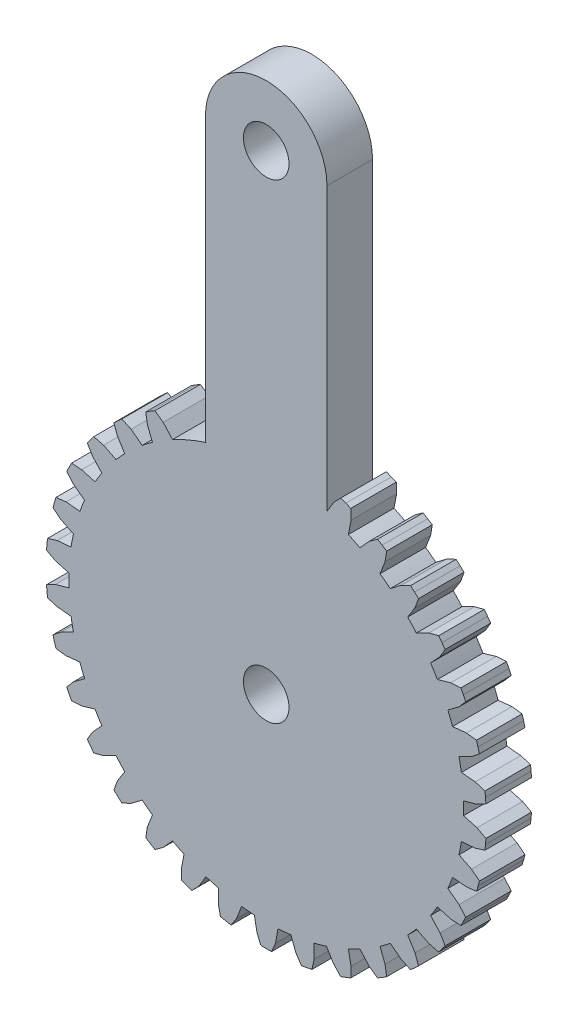
SolidWorks part; units mm, degrees
material "Chrome Stainless Steel"
ref_plane "Front Plane" through (0, 0, 0) normal (0, 0, 1) x (1, 0, 0)
ref_plane "Top Plane" through (0, 0, 0) normal (0, 1, 0) x (1, 0, 0)
ref_plane "Right Plane" through (0, 0, 0) normal (1, 0, 0) x (0, 0, -1)
sketch "Sketch1" plane through (0, 0, 0) normal (0, 0, 1) x (1, 0, 0)
  line L0 (0, 13) -> (0, 14.5) construction
  line L1 (-0.7768, 12.9768) -> (-0.6124, 13.879)
  line L2 (-0.6124, 13.879) -> (-0.3549, 14.4957)
  line L3 (-0.3549, 14.4957) -> (0, 14.5)
  line L4 (0.3549, 14.4957) -> (0, 14.5)
  line L5 (0.7768, 12.9768) -> (0.6124, 13.879)
  line L6 (0.6124, 13.879) -> (0.3549, 14.4957)
  line L7 (1.9483, 13.7552) -> (2.3147, 14.3141)
  line L8 (1.6209, 12.8986) -> (1.9483, 13.7552)
  line L9 (3.1522, 13.5302) -> (3.0124, 14.1836)
  line L10 (3.148, 12.6131) -> (3.1522, 13.5302)
  line L11 (3.0124, 14.1836) -> (2.6644, 14.2531)
  line L12 (2.3147, 14.3141) -> (2.6644, 14.2531)
  line L13 (4.4426, 13.163) -> (4.9055, 13.645)
  line L14 (3.9634, 12.3811) -> (4.4426, 13.163)
  line L15 (5.5847, 12.7206) -> (5.5674, 13.3886)
  line L16 (5.4121, 11.8199) -> (5.5847, 12.7206)
  line L17 (5.5674, 13.3886) -> (5.238, 13.5208)
  line L18 (4.9055, 13.645) -> (5.238, 13.5208)
  line L19 (6.7857, 12.1225) -> (7.3292, 12.5113)
  line L20 (6.1709, 11.442) -> (6.7857, 12.1225)
  line L21 (7.827, 11.4778) -> (7.9327, 12.1376)
  line L22 (7.4918, 10.6241) -> (7.827, 11.4778)
  line L23 (7.9327, 12.1376) -> (7.6333, 12.3281)
  line L24 (7.3292, 12.5113) -> (7.6333, 12.3281)
  line L25 (8.8977, 10.6693) -> (9.5034, 10.9515)
  line L26 (8.1683, 10.1133) -> (8.8977, 10.6693)
  line L27 (9.8028, 9.8441) -> (10.0279, 10.4733)
  line L28 (9.3165, 9.0666) -> (9.8028, 9.8441)
  line L29 (10.0279, 10.4733) -> (9.7686, 10.7156)
  line L30 (9.5034, 10.9515) -> (9.7686, 10.7156)
  line L31 (10.7066, 8.8526) -> (11.3539, 9.0188)
  line L32 (9.8876, 8.4402) -> (10.7066, 8.8526)
  line L33 (11.4447, 7.8753) -> (11.7817, 8.4524)
  line L34 (10.8238, 7.2004) -> (11.4447, 7.8753)
  line L35 (11.7817, 8.4524) -> (11.5712, 8.7382)
  line L36 (11.3539, 9.0188) -> (11.5712, 8.7382)
  line L37 (12.151, 6.7346) -> (12.8178, 6.779)
  line L38 (11.2701, 6.4796) -> (12.151, 6.7346)
  line L39 (12.6969, 5.6382) -> (13.1342, 6.1436)
  line L40 (11.9626, 5.0889) -> (12.6969, 5.6382)
  line L41 (13.1342, 6.1436) -> (12.9799, 6.4632)
  line L42 (12.8178, 6.779) -> (12.9799, 6.4632)
  line L43 (13.1816, 4.3872) -> (13.8452, 4.3083)
  line L44 (12.2688, 4.2984) -> (13.1816, 4.3872)
  line L45 (13.5168, 3.2092) -> (14.0394, 3.6256)
  line L46 (12.694, 2.8041) -> (13.5168, 3.2092)
  line L47 (14.0394, 3.6256) -> (13.9465, 3.9681)
  line L48 (13.8452, 4.3083) -> (13.9465, 3.9681)
  line L49 (13.7633, 1.8904) -> (14.4011, 1.6909)
  line L50 (12.8497, 1.9708) -> (13.7633, 1.8904)
  line L51 (13.8763, 0.6708) -> (14.4666, 0.9841)
  line L52 (12.9931, 0.4239) -> (13.8763, 0.6708)
  line L53 (14.4666, 0.9841) -> (14.4381, 1.3379)
  line L54 (14.4011, 1.6909) -> (14.4381, 1.3379)
  line L55 (13.8763, -0.6708) -> (14.4666, -0.9841)
  line L56 (12.9931, -0.4239) -> (13.8763, -0.6708)
  line L57 (13.7633, -1.8904) -> (14.4011, -1.6909)
  line L58 (12.8497, -1.9708) -> (13.7633, -1.8904)
  line L59 (14.4011, -1.6909) -> (14.4381, -1.3379)
  line L60 (14.4666, -0.9841) -> (14.4381, -1.3379)
  line L61 (13.5168, -3.2092) -> (14.0394, -3.6256)
  line L62 (12.694, -2.8041) -> (13.5168, -3.2092)
  line L63 (13.1816, -4.3872) -> (13.8452, -4.3083)
  line L64 (12.2688, -4.2984) -> (13.1816, -4.3872)
  line L65 (13.8452, -4.3083) -> (13.9465, -3.9681)
  line L66 (14.0394, -3.6256) -> (13.9465, -3.9681)
  line L67 (12.6969, -5.6382) -> (13.1342, -6.1436)
  line L68 (11.9626, -5.0889) -> (12.6969, -5.6382)
  line L69 (12.151, -6.7346) -> (12.8178, -6.779)
  line L70 (11.2701, -6.4796) -> (12.151, -6.7346)
  line L71 (12.8178, -6.779) -> (12.9799, -6.4632)
  line L72 (13.1342, -6.1436) -> (12.9799, -6.4632)
  line L73 (11.4447, -7.8753) -> (11.7817, -8.4524)
  line L74 (10.8238, -7.2004) -> (11.4447, -7.8753)
  line L75 (10.7066, -8.8526) -> (11.3539, -9.0188)
  line L76 (9.8876, -8.4402) -> (10.7066, -8.8526)
  line L77 (11.3539, -9.0188) -> (11.5712, -8.7382)
  line L78 (11.7817, -8.4524) -> (11.5712, -8.7382)
  line L79 (9.8028, -9.8441) -> (10.0279, -10.4733)
  line L80 (9.3165, -9.0666) -> (9.8028, -9.8441)
  line L81 (8.8977, -10.6693) -> (9.5034, -10.9515)
  line L82 (8.1683, -10.1133) -> (8.8977, -10.6693)
  line L83 (9.5034, -10.9515) -> (9.7686, -10.7156)
  line L84 (10.0279, -10.4733) -> (9.7686, -10.7156)
  line L85 (7.827, -11.4778) -> (7.9327, -12.1376)
  line L86 (7.4918, -10.6241) -> (7.827, -11.4778)
  line L87 (6.7857, -12.1225) -> (7.3292, -12.5113)
  line L88 (6.1709, -11.442) -> (6.7857, -12.1225)
  line L89 (7.3292, -12.5113) -> (7.6333, -12.3281)
  line L90 (7.9327, -12.1376) -> (7.6333, -12.3281)
  line L91 (5.5847, -12.7206) -> (5.5674, -13.3886)
  line L92 (5.4121, -11.8199) -> (5.5847, -12.7206)
  line L93 (4.4426, -13.163) -> (4.9055, -13.645)
  line L94 (3.9634, -12.3811) -> (4.4426, -13.163)
  line L95 (4.9055, -13.645) -> (5.238, -13.5208)
  line L96 (5.5674, -13.3886) -> (5.238, -13.5208)
  line L97 (3.1522, -13.5302) -> (3.0124, -14.1836)
  line L98 (3.148, -12.6131) -> (3.1522, -13.5302)
  line L99 (1.9483, -13.7552) -> (2.3147, -14.3141)
  line L100 (1.6209, -12.8986) -> (1.9483, -13.7552)
  line L101 (2.3147, -14.3141) -> (2.6644, -14.2531)
  line L102 (3.0124, -14.1836) -> (2.6644, -14.2531)
  line L103 (0.6124, -13.879) -> (0.3549, -14.4957)
  line L104 (0.7768, -12.9768) -> (0.6124, -13.879)
  line L105 (-0.6124, -13.879) -> (-0.3549, -14.4957)
  line L106 (-0.7768, -12.9768) -> (-0.6124, -13.879)
  line L107 (-0.3549, -14.4957) -> (0, -14.5)
  line L108 (0.3549, -14.4957) -> (0, -14.5)
  line L109 (-1.9483, -13.7552) -> (-2.3147, -14.3141)
  line L110 (-1.6209, -12.8986) -> (-1.9483, -13.7552)
  line L111 (-3.1522, -13.5302) -> (-3.0124, -14.1836)
  line L112 (-3.148, -12.6131) -> (-3.1522, -13.5302)
  line L113 (-3.0124, -14.1836) -> (-2.6644, -14.2531)
  line L114 (-2.3147, -14.3141) -> (-2.6644, -14.2531)
  line L115 (-4.4426, -13.163) -> (-4.9055, -13.645)
  line L116 (-3.9634, -12.3811) -> (-4.4426, -13.163)
  line L117 (-5.5847, -12.7206) -> (-5.5674, -13.3886)
  line L118 (-5.4121, -11.8199) -> (-5.5847, -12.7206)
  line L119 (-5.5674, -13.3886) -> (-5.238, -13.5208)
  line L120 (-4.9055, -13.645) -> (-5.238, -13.5208)
  line L121 (-6.7857, -12.1225) -> (-7.3292, -12.5113)
  line L122 (-6.1709, -11.442) -> (-6.7857, -12.1225)
  line L123 (-7.827, -11.4778) -> (-7.9327, -12.1376)
  line L124 (-7.4918, -10.6241) -> (-7.827, -11.4778)
  line L125 (-7.9327, -12.1376) -> (-7.6333, -12.3281)
  line L126 (-7.3292, -12.5113) -> (-7.6333, -12.3281)
  line L127 (-8.8977, -10.6693) -> (-9.5034, -10.9515)
  line L128 (-8.1683, -10.1133) -> (-8.8977, -10.6693)
  line L129 (-9.8028, -9.8441) -> (-10.0279, -10.4733)
  line L130 (-9.3165, -9.0666) -> (-9.8028, -9.8441)
  line L131 (-10.0279, -10.4733) -> (-9.7686, -10.7156)
  line L132 (-9.5034, -10.9515) -> (-9.7686, -10.7156)
  line L133 (-10.7066, -8.8526) -> (-11.3539, -9.0188)
  line L134 (-9.8876, -8.4402) -> (-10.7066, -8.8526)
  line L135 (-11.4447, -7.8753) -> (-11.7817, -8.4524)
  line L136 (-10.8238, -7.2004) -> (-11.4447, -7.8753)
  line L137 (-11.7817, -8.4524) -> (-11.5712, -8.7382)
  line L138 (-11.3539, -9.0188) -> (-11.5712, -8.7382)
  line L139 (-12.151, -6.7346) -> (-12.8178, -6.779)
  line L140 (-11.2701, -6.4796) -> (-12.151, -6.7346)
  line L141 (-12.6969, -5.6382) -> (-13.1342, -6.1436)
  line L142 (-11.9626, -5.0889) -> (-12.6969, -5.6382)
  line L143 (-13.1342, -6.1436) -> (-12.9799, -6.4632)
  line L144 (-12.8178, -6.779) -> (-12.9799, -6.4632)
  line L145 (-13.1816, -4.3872) -> (-13.8452, -4.3083)
  line L146 (-12.2688, -4.2984) -> (-13.1816, -4.3872)
  line L147 (-13.5168, -3.2092) -> (-14.0394, -3.6256)
  line L148 (-12.694, -2.8041) -> (-13.5168, -3.2092)
  line L149 (-14.0394, -3.6256) -> (-13.9465, -3.9681)
  line L150 (-13.8452, -4.3083) -> (-13.9465, -3.9681)
  line L151 (-13.7633, -1.8904) -> (-14.4011, -1.6909)
  line L152 (-12.8497, -1.9708) -> (-13.7633, -1.8904)
  line L153 (-13.8763, -0.6708) -> (-14.4666, -0.9841)
  line L154 (-12.9931, -0.4239) -> (-13.8763, -0.6708)
  line L155 (-14.4666, -0.9841) -> (-14.4381, -1.3379)
  line L156 (-14.4011, -1.6909) -> (-14.4381, -1.3379)
  line L157 (-13.8763, 0.6708) -> (-14.4666, 0.9841)
  line L158 (-12.9931, 0.4239) -> (-13.8763, 0.6708)
  line L159 (-13.7633, 1.8904) -> (-14.4011, 1.6909)
  line L160 (-12.8497, 1.9708) -> (-13.7633, 1.8904)
  line L161 (-14.4011, 1.6909) -> (-14.4381, 1.3379)
  line L162 (-14.4666, 0.9841) -> (-14.4381, 1.3379)
  line L163 (-13.5168, 3.2092) -> (-14.0394, 3.6256)
  line L164 (-12.694, 2.8041) -> (-13.5168, 3.2092)
  line L165 (-13.1816, 4.3872) -> (-13.8452, 4.3083)
  line L166 (-12.2688, 4.2984) -> (-13.1816, 4.3872)
  line L167 (-13.8452, 4.3083) -> (-13.9465, 3.9681)
  line L168 (-14.0394, 3.6256) -> (-13.9465, 3.9681)
  line L169 (-12.6969, 5.6382) -> (-13.1342, 6.1436)
  line L170 (-11.9626, 5.0889) -> (-12.6969, 5.6382)
  line L171 (-12.151, 6.7346) -> (-12.8178, 6.779)
  line L172 (-11.2701, 6.4796) -> (-12.151, 6.7346)
  line L173 (-12.8178, 6.779) -> (-12.9799, 6.4632)
  line L174 (-13.1342, 6.1436) -> (-12.9799, 6.4632)
  line L175 (-11.4447, 7.8753) -> (-11.7817, 8.4524)
  line L176 (-10.8238, 7.2004) -> (-11.4447, 7.8753)
  line L177 (-10.7066, 8.8526) -> (-11.3539, 9.0188)
  line L178 (-9.8876, 8.4402) -> (-10.7066, 8.8526)
  line L179 (-11.3539, 9.0188) -> (-11.5712, 8.7382)
  line L180 (-11.7817, 8.4524) -> (-11.5712, 8.7382)
  line L181 (-9.8028, 9.8441) -> (-10.0279, 10.4733)
  line L182 (-9.3165, 9.0666) -> (-9.8028, 9.8441)
  line L183 (-8.8977, 10.6693) -> (-9.5034, 10.9515)
  line L184 (-8.1683, 10.1133) -> (-8.8977, 10.6693)
  line L185 (-9.5034, 10.9515) -> (-9.7686, 10.7156)
  line L186 (-10.0279, 10.4733) -> (-9.7686, 10.7156)
  line L187 (-7.827, 11.4778) -> (-7.9327, 12.1376)
  line L188 (-7.4918, 10.6241) -> (-7.827, 11.4778)
  line L189 (-6.7857, 12.1225) -> (-7.3292, 12.5113)
  line L190 (-6.1709, 11.442) -> (-6.7857, 12.1225)
  line L191 (-7.3292, 12.5113) -> (-7.6333, 12.3281)
  line L192 (-7.9327, 12.1376) -> (-7.6333, 12.3281)
  line L193 (-5.5847, 12.7206) -> (-5.5674, 13.3886)
  line L194 (-5.4121, 11.8199) -> (-5.5847, 12.7206)
  line L195 (-4.4426, 13.163) -> (-4.9055, 13.645)
  line L196 (-3.9634, 12.3811) -> (-4.4426, 13.163)
  line L197 (-4.9055, 13.645) -> (-5.238, 13.5208)
  line L198 (-5.5674, 13.3886) -> (-5.238, 13.5208)
  line L199 (-3.1522, 13.5302) -> (-3.0124, 14.1836)
  line L200 (-3.148, 12.6131) -> (-3.1522, 13.5302)
  line L201 (-1.9483, 13.7552) -> (-2.3147, 14.3141)
  line L202 (-1.6209, 12.8986) -> (-1.9483, 13.7552)
  line L203 (-2.3147, 14.3141) -> (-2.6644, 14.2531)
  line L204 (-3.0124, 14.1836) -> (-2.6644, 14.2531)
  circle A0 centre (0, 0) radius 13
  circle A1 centre (0, 0) radius 14.5
  point P246 (0, 0)
  dimension "D1" = 29
  dimension "D2" = 26
  dimension "D3" = 0.3549
  dimension "D4" = 0.6682
  dimension "D5" = 0.9171
extrude "Boss-Extrude1" add sketch "Sketch1" along normal blind 3
sketch "Sketch2" plane through (0, 0, 3) normal (0, 0, 1) x (1, 0, 0)
  circle A0 centre (0, 0) radius 1.5
  dimension "D1" = 3
extrude "Cut-Extrude1" cut sketch "Sketch2" against normal blind 7
sketch "Sketch4" plane through (0, 0, 3) normal (0, 0, 1) x (1, 0, 0)
  line L0 (0, 0) -> (0, 31) construction
  line L1 (-4, 0) -> (-4, 31)
  line L2 (4, 0) -> (4, 31)
  line L3 (3.148, 12.6131) -> (3.1522, 13.5302)
  line L4 (3.1522, 13.5302) -> (3.0124, 14.1836)
  line L5 (3.0124, 14.1836) -> (2.6644, 14.2531)
  line L6 (2.6644, 14.2531) -> (2.3147, 14.3141)
  line L7 (2.3147, 14.3141) -> (1.9483, 13.7552)
  line L8 (1.9483, 13.7552) -> (1.6209, 12.8986)
  line L9 (5.4121, 11.8199) -> (5.5847, 12.7206)
  line L10 (5.5847, 12.7206) -> (5.5674, 13.3886)
  line L11 (5.5674, 13.3886) -> (5.238, 13.5208)
  line L12 (5.238, 13.5208) -> (4.9055, 13.645)
  line L13 (4.9055, 13.645) -> (4.4426, 13.163)
  line L14 (4.4426, 13.163) -> (3.9634, 12.3811)
  line L15 (7.4918, 10.6241) -> (7.827, 11.4778)
  line L16 (7.827, 11.4778) -> (7.9327, 12.1376)
  line L17 (7.9327, 12.1376) -> (7.6333, 12.3281)
  line L18 (7.6333, 12.3281) -> (7.3292, 12.5113)
  line L19 (7.3292, 12.5113) -> (6.7857, 12.1225)
  line L20 (6.7857, 12.1225) -> (6.1709, 11.442)
  line L21 (9.3165, 9.0666) -> (9.8028, 9.8441)
  line L22 (9.8028, 9.8441) -> (10.0279, 10.4733)
  line L23 (10.0279, 10.4733) -> (9.7686, 10.7156)
  line L24 (9.7686, 10.7156) -> (9.5034, 10.9515)
  line L25 (9.5034, 10.9515) -> (8.8977, 10.6693)
  line L26 (8.8977, 10.6693) -> (8.1683, 10.1133)
  line L27 (10.8238, 7.2004) -> (11.4447, 7.8753)
  line L28 (11.4447, 7.8753) -> (11.7817, 8.4524)
  line L29 (11.7817, 8.4524) -> (11.5712, 8.7382)
  line L30 (11.5712, 8.7382) -> (11.3539, 9.0188)
  line L31 (11.3539, 9.0188) -> (10.7066, 8.8526)
  line L32 (10.7066, 8.8526) -> (9.8876, 8.4402)
  line L33 (11.9626, 5.0889) -> (12.6969, 5.6382)
  line L34 (12.6969, 5.6382) -> (13.1342, 6.1436)
  line L35 (13.1342, 6.1436) -> (12.9799, 6.4632)
  line L36 (12.9799, 6.4632) -> (12.8178, 6.779)
  line L37 (12.8178, 6.779) -> (12.151, 6.7346)
  line L38 (12.151, 6.7346) -> (11.2701, 6.4796)
  line L39 (12.694, 2.8041) -> (13.5168, 3.2092)
  line L40 (13.5168, 3.2092) -> (14.0394, 3.6256)
  line L41 (14.0394, 3.6256) -> (13.9465, 3.9681)
  line L42 (13.9465, 3.9681) -> (13.8452, 4.3083)
  line L43 (13.8452, 4.3083) -> (13.1816, 4.3872)
  line L44 (13.1816, 4.3872) -> (12.2688, 4.2984)
  line L45 (12.9931, 0.4239) -> (13.8763, 0.6708)
  line L46 (13.8763, 0.6708) -> (14.4666, 0.9841)
  line L47 (14.4666, 0.9841) -> (14.4381, 1.3379)
  line L48 (14.4381, 1.3379) -> (14.4011, 1.6909)
  line L49 (14.4011, 1.6909) -> (13.7633, 1.8904)
  line L50 (13.7633, 1.8904) -> (12.8497, 1.9708)
  line L51 (12.8497, -1.9708) -> (13.7633, -1.8904)
  line L52 (13.7633, -1.8904) -> (14.4011, -1.6909)
  line L53 (14.4011, -1.6909) -> (14.4381, -1.3379)
  line L54 (14.4381, -1.3379) -> (14.4666, -0.9841)
  line L55 (14.4666, -0.9841) -> (13.8763, -0.6708)
  line L56 (13.8763, -0.6708) -> (12.9931, -0.4239)
  line L57 (12.2688, -4.2984) -> (13.1816, -4.3872)
  line L58 (13.1816, -4.3872) -> (13.8452, -4.3083)
  line L59 (13.8452, -4.3083) -> (13.9465, -3.9681)
  line L60 (13.9465, -3.9681) -> (14.0394, -3.6256)
  line L61 (14.0394, -3.6256) -> (13.5168, -3.2092)
  line L62 (13.5168, -3.2092) -> (12.694, -2.8041)
  line L63 (11.2701, -6.4796) -> (12.151, -6.7346)
  line L64 (12.151, -6.7346) -> (12.8178, -6.779)
  line L65 (12.8178, -6.779) -> (12.9799, -6.4632)
  line L66 (12.9799, -6.4632) -> (13.1342, -6.1436)
  line L67 (13.1342, -6.1436) -> (12.6969, -5.6382)
  line L68 (12.6969, -5.6382) -> (11.9626, -5.0889)
  line L69 (9.8876, -8.4402) -> (10.7066, -8.8526)
  line L70 (10.7066, -8.8526) -> (11.3539, -9.0188)
  line L71 (11.3539, -9.0188) -> (11.5712, -8.7382)
  line L72 (11.5712, -8.7382) -> (11.7817, -8.4524)
  line L73 (11.7817, -8.4524) -> (11.4447, -7.8753)
  line L74 (11.4447, -7.8753) -> (10.8238, -7.2004)
  line L75 (8.1683, -10.1133) -> (8.8977, -10.6693)
  line L76 (8.8977, -10.6693) -> (9.5034, -10.9515)
  line L77 (9.5034, -10.9515) -> (9.7686, -10.7156)
  line L78 (9.7686, -10.7156) -> (10.0279, -10.4733)
  line L79 (10.0279, -10.4733) -> (9.8028, -9.8441)
  line L80 (9.8028, -9.8441) -> (9.3165, -9.0666)
  line L81 (6.1709, -11.442) -> (6.7857, -12.1225)
  line L82 (6.7857, -12.1225) -> (7.3292, -12.5113)
  line L83 (7.3292, -12.5113) -> (7.6333, -12.3281)
  line L84 (7.6333, -12.3281) -> (7.9327, -12.1376)
  line L85 (7.9327, -12.1376) -> (7.827, -11.4778)
  line L86 (7.827, -11.4778) -> (7.4918, -10.6241)
  line L87 (3.9634, -12.3811) -> (4.4426, -13.163)
  line L88 (4.4426, -13.163) -> (4.9055, -13.645)
  line L89 (4.9055, -13.645) -> (5.238, -13.5208)
  line L90 (5.238, -13.5208) -> (5.5674, -13.3886)
  line L91 (5.5674, -13.3886) -> (5.5847, -12.7206)
  line L92 (5.5847, -12.7206) -> (5.4121, -11.8199)
  line L93 (1.6209, -12.8986) -> (1.9483, -13.7552)
  line L94 (1.9483, -13.7552) -> (2.3147, -14.3141)
  line L95 (2.3147, -14.3141) -> (2.6644, -14.2531)
  line L96 (2.6644, -14.2531) -> (3.0124, -14.1836)
  line L97 (3.0124, -14.1836) -> (3.1522, -13.5302)
  line L98 (3.1522, -13.5302) -> (3.148, -12.6131)
  line L99 (-0.7768, -12.9768) -> (-0.6124, -13.879)
  line L100 (-0.6124, -13.879) -> (-0.3549, -14.4957)
  line L101 (-0.3549, -14.4957) -> (0, -14.5)
  line L102 (0, -14.5) -> (0.3549, -14.4957)
  line L103 (0.3549, -14.4957) -> (0.6124, -13.879)
  line L104 (0.6124, -13.879) -> (0.7768, -12.9768)
  line L105 (-3.148, -12.6131) -> (-3.1522, -13.5302)
  line L106 (-3.1522, -13.5302) -> (-3.0124, -14.1836)
  line L107 (-3.0124, -14.1836) -> (-2.6644, -14.2531)
  line L108 (-2.6644, -14.2531) -> (-2.3147, -14.3141)
  line L109 (-2.3147, -14.3141) -> (-1.9483, -13.7552)
  line L110 (-1.9483, -13.7552) -> (-1.6209, -12.8986)
  line L111 (-5.4121, -11.8199) -> (-5.5847, -12.7206)
  line L112 (-5.5847, -12.7206) -> (-5.5674, -13.3886)
  line L113 (-5.5674, -13.3886) -> (-5.238, -13.5208)
  line L114 (-5.238, -13.5208) -> (-4.9055, -13.645)
  line L115 (-4.9055, -13.645) -> (-4.4426, -13.163)
  line L116 (-4.4426, -13.163) -> (-3.9634, -12.3811)
  line L117 (0.3549, 14.4957) -> (0, 14.5)
  line L118 (0, 14.5) -> (-0.3549, 14.4957)
  line L119 (-0.3549, 14.4957) -> (-0.6124, 13.879)
  line L120 (-0.6124, 13.879) -> (-0.7768, 12.9768)
  line L121 (-3.148, -12.6131) -> (-3.1522, -13.5302)
  line L122 (-3.1522, -13.5302) -> (-3.0124, -14.1836)
  line L123 (-3.0124, -14.1836) -> (-2.6644, -14.2531)
  line L124 (-2.6644, -14.2531) -> (-2.3147, -14.3141)
  line L125 (-2.3147, -14.3141) -> (-1.9483, -13.7552)
  line L126 (-1.9483, -13.7552) -> (-1.6209, -12.8986)
  line L127 (-0.7768, -12.9768) -> (-0.6124, -13.879)
  line L128 (-0.6124, -13.879) -> (-0.3549, -14.4957)
  line L129 (-0.3549, -14.4957) -> (0, -14.5)
  line L130 (0, -14.5) -> (0.3549, -14.4957)
  line L131 (0.3549, -14.4957) -> (0.6124, -13.879)
  line L132 (0.6124, -13.879) -> (0.7768, -12.9768)
  line L133 (1.6209, -12.8986) -> (1.9483, -13.7552)
  line L134 (1.9483, -13.7552) -> (2.3147, -14.3141)
  line L135 (2.3147, -14.3141) -> (2.6644, -14.2531)
  line L136 (2.6644, -14.2531) -> (3.0124, -14.1836)
  line L137 (3.0124, -14.1836) -> (3.1522, -13.5302)
  line L138 (3.1522, -13.5302) -> (3.148, -12.6131)
  line L139 (3.9634, -12.3811) -> (4.4426, -13.163)
  line L140 (4.4426, -13.163) -> (4.9055, -13.645)
  line L141 (4.9055, -13.645) -> (5.238, -13.5208)
  line L142 (5.238, -13.5208) -> (5.5674, -13.3886)
  line L143 (5.5674, -13.3886) -> (5.5847, -12.7206)
  line L144 (5.5847, -12.7206) -> (5.4121, -11.8199)
  line L145 (6.1709, -11.442) -> (6.7857, -12.1225)
  line L146 (6.7857, -12.1225) -> (7.3292, -12.5113)
  line L147 (7.3292, -12.5113) -> (7.6333, -12.3281)
  line L148 (7.6333, -12.3281) -> (7.9327, -12.1376)
  line L149 (7.9327, -12.1376) -> (7.827, -11.4778)
  line L150 (7.827, -11.4778) -> (7.4918, -10.6241)
  line L151 (8.1683, -10.1133) -> (8.8977, -10.6693)
  line L152 (8.8977, -10.6693) -> (9.5034, -10.9515)
  line L153 (9.5034, -10.9515) -> (9.7686, -10.7156)
  line L154 (9.7686, -10.7156) -> (10.0279, -10.4733)
  line L155 (10.0279, -10.4733) -> (9.8028, -9.8441)
  line L156 (9.8028, -9.8441) -> (9.3165, -9.0666)
  line L157 (9.8876, -8.4402) -> (10.7066, -8.8526)
  line L158 (10.7066, -8.8526) -> (11.3539, -9.0188)
  line L159 (11.3539, -9.0188) -> (11.5712, -8.7382)
  line L160 (11.5712, -8.7382) -> (11.7817, -8.4524)
  line L161 (11.7817, -8.4524) -> (11.4447, -7.8753)
  line L162 (11.4447, -7.8753) -> (10.8238, -7.2004)
  line L163 (11.2701, -6.4796) -> (12.151, -6.7346)
  line L164 (12.151, -6.7346) -> (12.8178, -6.779)
  line L165 (12.8178, -6.779) -> (12.9799, -6.4632)
  line L166 (12.9799, -6.4632) -> (13.1342, -6.1436)
  line L167 (13.1342, -6.1436) -> (12.6969, -5.6382)
  line L168 (12.6969, -5.6382) -> (11.9626, -5.0889)
  line L169 (12.2688, -4.2984) -> (13.1816, -4.3872)
  line L170 (13.1816, -4.3872) -> (13.8452, -4.3083)
  line L171 (13.8452, -4.3083) -> (13.9465, -3.9681)
  line L172 (13.9465, -3.9681) -> (14.0394, -3.6256)
  line L173 (14.0394, -3.6256) -> (13.5168, -3.2092)
  line L174 (13.5168, -3.2092) -> (12.694, -2.8041)
  line L175 (12.8497, -1.9708) -> (13.7633, -1.8904)
  line L176 (13.7633, -1.8904) -> (14.4011, -1.6909)
  line L177 (14.4011, -1.6909) -> (14.4381, -1.3379)
  line L178 (14.4381, -1.3379) -> (14.4666, -0.9841)
  line L179 (14.4666, -0.9841) -> (13.8763, -0.6708)
  line L180 (13.8763, -0.6708) -> (12.9931, -0.4239)
  line L181 (12.9931, 0.4239) -> (13.8763, 0.6708)
  line L182 (13.8763, 0.6708) -> (14.4666, 0.9841)
  line L183 (14.4666, 0.9841) -> (14.4381, 1.3379)
  line L184 (14.4381, 1.3379) -> (14.4011, 1.6909)
  line L185 (14.4011, 1.6909) -> (13.7633, 1.8904)
  line L186 (13.7633, 1.8904) -> (12.8497, 1.9708)
  line L187 (12.694, 2.8041) -> (13.5168, 3.2092)
  line L188 (13.5168, 3.2092) -> (14.0394, 3.6256)
  line L189 (14.0394, 3.6256) -> (13.9465, 3.9681)
  line L190 (13.9465, 3.9681) -> (13.8452, 4.3083)
  line L191 (13.8452, 4.3083) -> (13.1816, 4.3872)
  line L192 (13.1816, 4.3872) -> (12.2688, 4.2984)
  line L193 (11.9626, 5.0889) -> (12.6969, 5.6382)
  line L194 (12.6969, 5.6382) -> (13.1342, 6.1436)
  line L195 (13.1342, 6.1436) -> (12.9799, 6.4632)
  line L196 (12.9799, 6.4632) -> (12.8178, 6.779)
  line L197 (12.8178, 6.779) -> (12.151, 6.7346)
  line L198 (12.151, 6.7346) -> (11.2701, 6.4796)
  line L199 (10.8238, 7.2004) -> (11.4447, 7.8753)
  line L200 (11.4447, 7.8753) -> (11.7817, 8.4524)
  line L201 (11.7817, 8.4524) -> (11.5712, 8.7382)
  line L202 (11.5712, 8.7382) -> (11.3539, 9.0188)
  line L203 (11.3539, 9.0188) -> (10.7066, 8.8526)
  line L204 (10.7066, 8.8526) -> (9.8876, 8.4402)
  line L205 (9.3165, 9.0666) -> (9.8028, 9.8441)
  line L206 (9.8028, 9.8441) -> (10.0279, 10.4733)
  line L207 (10.0279, 10.4733) -> (9.7686, 10.7156)
  line L208 (9.7686, 10.7156) -> (9.5034, 10.9515)
  line L209 (9.5034, 10.9515) -> (8.8977, 10.6693)
  line L210 (8.8977, 10.6693) -> (8.1683, 10.1133)
  line L211 (7.4918, 10.6241) -> (7.827, 11.4778)
  line L212 (7.827, 11.4778) -> (7.9327, 12.1376)
  line L213 (7.9327, 12.1376) -> (7.6333, 12.3281)
  line L214 (7.6333, 12.3281) -> (7.3292, 12.5113)
  line L215 (7.3292, 12.5113) -> (6.7857, 12.1225)
  line L216 (6.7857, 12.1225) -> (6.1709, 11.442)
  line L217 (5.4121, 11.8199) -> (5.5847, 12.7206)
  line L218 (5.5847, 12.7206) -> (5.5674, 13.3886)
  line L219 (5.5674, 13.3886) -> (5.238, 13.5208)
  line L220 (5.238, 13.5208) -> (4.9055, 13.645)
  line L221 (4.9055, 13.645) -> (4.4426, 13.163)
  line L222 (4.4426, 13.163) -> (3.9634, 12.3811)
  line L223 (3.148, 12.6131) -> (3.1522, 13.5302)
  line L224 (3.1522, 13.5302) -> (3.0124, 14.1836)
  line L225 (3.0124, 14.1836) -> (2.6644, 14.2531)
  line L226 (2.6644, 14.2531) -> (2.3147, 14.3141)
  line L227 (2.3147, 14.3141) -> (1.9483, 13.7552)
  line L228 (1.9483, 13.7552) -> (1.6209, 12.8986)
  line L229 (0.7768, 12.9768) -> (0.6124, 13.879)
  line L230 (0.6124, 13.879) -> (0.3549, 14.4957)
  line L231 (0.3549, 14.4957) -> (0, 14.5)
  line L232 (0, 14.5) -> (-0.3549, 14.4957)
  line L233 (-0.3549, 14.4957) -> (-0.6124, 13.879)
  line L234 (-0.6124, 13.879) -> (-0.7768, 12.9768)
  line L235 (-3.148, -12.6131) -> (-3.1522, -13.5302)
  line L236 (-3.1522, -13.5302) -> (-3.0124, -14.1836)
  line L237 (-3.0124, -14.1836) -> (-2.6644, -14.2531)
  line L238 (-2.6644, -14.2531) -> (-2.3147, -14.3141)
  line L239 (-2.3147, -14.3141) -> (-1.9483, -13.7552)
  line L240 (-1.9483, -13.7552) -> (-1.6209, -12.8986)
  line L241 (-0.7768, -12.9768) -> (-0.6124, -13.879)
  line L242 (-0.6124, -13.879) -> (-0.3549, -14.4957)
  line L243 (-0.3549, -14.4957) -> (0, -14.5)
  line L244 (0, -14.5) -> (0.3549, -14.4957)
  line L245 (0.3549, -14.4957) -> (0.6124, -13.879)
  line L246 (0.6124, -13.879) -> (0.7768, -12.9768)
  line L247 (1.6209, -12.8986) -> (1.9483, -13.7552)
  line L248 (1.9483, -13.7552) -> (2.3147, -14.3141)
  line L249 (2.3147, -14.3141) -> (2.6644, -14.2531)
  line L250 (2.6644, -14.2531) -> (3.0124, -14.1836)
  line L251 (3.0124, -14.1836) -> (3.1522, -13.5302)
  line L252 (3.1522, -13.5302) -> (3.148, -12.6131)
  line L253 (3.9634, -12.3811) -> (4.4426, -13.163)
  line L254 (4.4426, -13.163) -> (4.9055, -13.645)
  line L255 (4.9055, -13.645) -> (5.238, -13.5208)
  line L256 (5.238, -13.5208) -> (5.5674, -13.3886)
  line L257 (5.5674, -13.3886) -> (5.5847, -12.7206)
  line L258 (5.5847, -12.7206) -> (5.4121, -11.8199)
  line L259 (6.1709, -11.442) -> (6.7857, -12.1225)
  line L260 (6.7857, -12.1225) -> (7.3292, -12.5113)
  line L261 (7.3292, -12.5113) -> (7.6333, -12.3281)
  line L262 (7.6333, -12.3281) -> (7.9327, -12.1376)
  line L263 (7.9327, -12.1376) -> (7.827, -11.4778)
  line L264 (7.827, -11.4778) -> (7.4918, -10.6241)
  line L265 (8.1683, -10.1133) -> (8.8977, -10.6693)
  line L266 (8.8977, -10.6693) -> (9.5034, -10.9515)
  line L267 (9.5034, -10.9515) -> (9.7686, -10.7156)
  line L268 (9.7686, -10.7156) -> (10.0279, -10.4733)
  line L269 (10.0279, -10.4733) -> (9.8028, -9.8441)
  line L270 (9.8028, -9.8441) -> (9.3165, -9.0666)
  line L271 (9.8876, -8.4402) -> (10.7066, -8.8526)
  line L272 (10.7066, -8.8526) -> (11.3539, -9.0188)
  line L273 (11.3539, -9.0188) -> (11.5712, -8.7382)
  line L274 (11.5712, -8.7382) -> (11.7817, -8.4524)
  line L275 (11.7817, -8.4524) -> (11.4447, -7.8753)
  line L276 (11.4447, -7.8753) -> (10.8238, -7.2004)
  line L277 (11.2701, -6.4796) -> (12.151, -6.7346)
  line L278 (12.151, -6.7346) -> (12.8178, -6.779)
  line L279 (12.8178, -6.779) -> (12.9799, -6.4632)
  line L280 (12.9799, -6.4632) -> (13.1342, -6.1436)
  line L281 (13.1342, -6.1436) -> (12.6969, -5.6382)
  line L282 (12.6969, -5.6382) -> (11.9626, -5.0889)
  line L283 (12.2688, -4.2984) -> (13.1816, -4.3872)
  line L284 (13.1816, -4.3872) -> (13.8452, -4.3083)
  line L285 (13.8452, -4.3083) -> (13.9465, -3.9681)
  line L286 (13.9465, -3.9681) -> (14.0394, -3.6256)
  line L287 (14.0394, -3.6256) -> (13.5168, -3.2092)
  line L288 (13.5168, -3.2092) -> (12.694, -2.8041)
  line L289 (12.8497, -1.9708) -> (13.7633, -1.8904)
  line L290 (13.7633, -1.8904) -> (14.4011, -1.6909)
  line L291 (14.4011, -1.6909) -> (14.4381, -1.3379)
  line L292 (14.4381, -1.3379) -> (14.4666, -0.9841)
  line L293 (14.4666, -0.9841) -> (13.8763, -0.6708)
  line L294 (13.8763, -0.6708) -> (12.9931, -0.4239)
  line L295 (12.9931, 0.4239) -> (13.8763, 0.6708)
  line L296 (13.8763, 0.6708) -> (14.4666, 0.9841)
  line L297 (14.4666, 0.9841) -> (14.4381, 1.3379)
  line L298 (14.4381, 1.3379) -> (14.4011, 1.6909)
  line L299 (14.4011, 1.6909) -> (13.7633, 1.8904)
  line L300 (13.7633, 1.8904) -> (12.8497, 1.9708)
  line L301 (12.694, 2.8041) -> (13.5168, 3.2092)
  line L302 (13.5168, 3.2092) -> (14.0394, 3.6256)
  line L303 (14.0394, 3.6256) -> (13.9465, 3.9681)
  line L304 (13.9465, 3.9681) -> (13.8452, 4.3083)
  line L305 (13.8452, 4.3083) -> (13.1816, 4.3872)
  line L306 (13.1816, 4.3872) -> (12.2688, 4.2984)
  line L307 (11.9626, 5.0889) -> (12.6969, 5.6382)
  line L308 (12.6969, 5.6382) -> (13.1342, 6.1436)
  line L309 (13.1342, 6.1436) -> (12.9799, 6.4632)
  line L310 (12.9799, 6.4632) -> (12.8178, 6.779)
  line L311 (12.8178, 6.779) -> (12.151, 6.7346)
  line L312 (12.151, 6.7346) -> (11.2701, 6.4796)
  line L313 (10.8238, 7.2004) -> (11.4447, 7.8753)
  line L314 (11.4447, 7.8753) -> (11.7817, 8.4524)
  line L315 (11.7817, 8.4524) -> (11.5712, 8.7382)
  line L316 (11.5712, 8.7382) -> (11.3539, 9.0188)
  line L317 (11.3539, 9.0188) -> (10.7066, 8.8526)
  line L318 (10.7066, 8.8526) -> (9.8876, 8.4402)
  line L319 (9.3165, 9.0666) -> (9.8028, 9.8441)
  line L320 (9.8028, 9.8441) -> (10.0279, 10.4733)
  line L321 (10.0279, 10.4733) -> (9.7686, 10.7156)
  line L322 (9.7686, 10.7156) -> (9.5034, 10.9515)
  line L323 (9.5034, 10.9515) -> (8.8977, 10.6693)
  line L324 (8.8977, 10.6693) -> (8.1683, 10.1133)
  line L325 (7.4918, 10.6241) -> (7.827, 11.4778)
  line L326 (7.827, 11.4778) -> (7.9327, 12.1376)
  line L327 (7.9327, 12.1376) -> (7.6333, 12.3281)
  line L328 (7.6333, 12.3281) -> (7.3292, 12.5113)
  line L329 (7.3292, 12.5113) -> (6.7857, 12.1225)
  line L330 (6.7857, 12.1225) -> (6.1709, 11.442)
  line L331 (5.4121, 11.8199) -> (5.5847, 12.7206)
  line L332 (5.5847, 12.7206) -> (5.5674, 13.3886)
  line L333 (5.5674, 13.3886) -> (5.238, 13.5208)
  line L334 (5.238, 13.5208) -> (4.9055, 13.645)
  line L335 (4.9055, 13.645) -> (4.4426, 13.163)
  line L336 (4.4426, 13.163) -> (3.9634, 12.3811)
  line L337 (3.148, 12.6131) -> (3.1522, 13.5302)
  line L338 (3.1522, 13.5302) -> (3.0124, 14.1836)
  line L339 (3.0124, 14.1836) -> (2.6644, 14.2531)
  line L340 (2.6644, 14.2531) -> (2.3147, 14.3141)
  line L341 (2.3147, 14.3141) -> (1.9483, 13.7552)
  line L342 (1.9483, 13.7552) -> (1.6209, 12.8986)
  line L343 (0.7768, 12.9768) -> (0.6124, 13.879)
  line L344 (0.6124, 13.879) -> (0.3549, 14.4957)
  line L345 (-7.4918, -10.6241) -> (-7.827, -11.4778)
  line L346 (-7.827, -11.4778) -> (-7.9327, -12.1376)
  line L347 (-7.9327, -12.1376) -> (-7.6333, -12.3281)
  line L348 (-7.6333, -12.3281) -> (-7.3292, -12.5113)
  line L349 (-7.3292, -12.5113) -> (-6.7857, -12.1225)
  line L350 (-6.7857, -12.1225) -> (-6.1709, -11.442)
  line L351 (-9.3165, -9.0666) -> (-9.8028, -9.8441)
  line L352 (-9.8028, -9.8441) -> (-10.0279, -10.4733)
  line L353 (-10.0279, -10.4733) -> (-9.7686, -10.7156)
  line L354 (-9.7686, -10.7156) -> (-9.5034, -10.9515)
  line L355 (-9.5034, -10.9515) -> (-8.8977, -10.6693)
  line L356 (-8.8977, -10.6693) -> (-8.1683, -10.1133)
  line L357 (-10.8238, -7.2004) -> (-11.4447, -7.8753)
  line L358 (-11.4447, -7.8753) -> (-11.7817, -8.4524)
  line L359 (-11.7817, -8.4524) -> (-11.5712, -8.7382)
  line L360 (-11.5712, -8.7382) -> (-11.3539, -9.0188)
  line L361 (-11.3539, -9.0188) -> (-10.7066, -8.8526)
  line L362 (-10.7066, -8.8526) -> (-9.8876, -8.4402)
  line L363 (-11.9626, -5.0889) -> (-12.6969, -5.6382)
  line L364 (-12.6969, -5.6382) -> (-13.1342, -6.1436)
  line L365 (-13.1342, -6.1436) -> (-12.9799, -6.4632)
  line L366 (-12.9799, -6.4632) -> (-12.8178, -6.779)
  line L367 (-12.8178, -6.779) -> (-12.151, -6.7346)
  line L368 (-12.151, -6.7346) -> (-11.2701, -6.4796)
  line L369 (-12.694, -2.8041) -> (-13.5168, -3.2092)
  line L370 (-13.5168, -3.2092) -> (-14.0394, -3.6256)
  line L371 (-14.0394, -3.6256) -> (-13.9465, -3.9681)
  line L372 (-13.9465, -3.9681) -> (-13.8452, -4.3083)
  line L373 (-13.8452, -4.3083) -> (-13.1816, -4.3872)
  line L374 (-13.1816, -4.3872) -> (-12.2688, -4.2984)
  line L375 (-12.9931, -0.4239) -> (-13.8763, -0.6708)
  line L376 (-13.8763, -0.6708) -> (-14.4666, -0.9841)
  line L377 (-14.4666, -0.9841) -> (-14.4381, -1.3379)
  line L378 (-14.4381, -1.3379) -> (-14.4011, -1.6909)
  line L379 (-14.4011, -1.6909) -> (-13.7633, -1.8904)
  line L380 (-13.7633, -1.8904) -> (-12.8497, -1.9708)
  line L381 (-12.8497, 1.9708) -> (-13.7633, 1.8904)
  line L382 (-13.7633, 1.8904) -> (-14.4011, 1.6909)
  line L383 (-14.4011, 1.6909) -> (-14.4381, 1.3379)
  line L384 (-14.4381, 1.3379) -> (-14.4666, 0.9841)
  line L385 (-14.4666, 0.9841) -> (-13.8763, 0.6708)
  line L386 (-13.8763, 0.6708) -> (-12.9931, 0.4239)
  line L387 (-12.2688, 4.2984) -> (-13.1816, 4.3872)
  line L388 (-13.1816, 4.3872) -> (-13.8452, 4.3083)
  line L389 (-13.8452, 4.3083) -> (-13.9465, 3.9681)
  line L390 (-13.9465, 3.9681) -> (-14.0394, 3.6256)
  line L391 (-14.0394, 3.6256) -> (-13.5168, 3.2092)
  line L392 (-13.5168, 3.2092) -> (-12.694, 2.8041)
  line L393 (-11.2701, 6.4796) -> (-12.151, 6.7346)
  line L394 (-12.151, 6.7346) -> (-12.8178, 6.779)
  line L395 (-12.8178, 6.779) -> (-12.9799, 6.4632)
  line L396 (-12.9799, 6.4632) -> (-13.1342, 6.1436)
  line L397 (-13.1342, 6.1436) -> (-12.6969, 5.6382)
  line L398 (-12.6969, 5.6382) -> (-11.9626, 5.0889)
  line L399 (-9.8876, 8.4402) -> (-10.7066, 8.8526)
  line L400 (-10.7066, 8.8526) -> (-11.3539, 9.0188)
  line L401 (-11.3539, 9.0188) -> (-11.5712, 8.7382)
  line L402 (-11.5712, 8.7382) -> (-11.7817, 8.4524)
  line L403 (-11.7817, 8.4524) -> (-11.4447, 7.8753)
  line L404 (-11.4447, 7.8753) -> (-10.8238, 7.2004)
  line L405 (-8.1683, 10.1133) -> (-8.8977, 10.6693)
  line L406 (-8.8977, 10.6693) -> (-9.5034, 10.9515)
  line L407 (-9.5034, 10.9515) -> (-9.7686, 10.7156)
  line L408 (-9.7686, 10.7156) -> (-10.0279, 10.4733)
  line L409 (-10.0279, 10.4733) -> (-9.8028, 9.8441)
  line L410 (-9.8028, 9.8441) -> (-9.3165, 9.0666)
  line L411 (-6.1709, 11.442) -> (-6.7857, 12.1225)
  line L412 (-6.7857, 12.1225) -> (-7.3292, 12.5113)
  line L413 (-7.3292, 12.5113) -> (-7.6333, 12.3281)
  line L414 (-7.6333, 12.3281) -> (-7.9327, 12.1376)
  line L415 (-7.9327, 12.1376) -> (-7.827, 11.4778)
  line L416 (-7.827, 11.4778) -> (-7.4918, 10.6241)
  line L417 (-3.9634, 12.3811) -> (-4.4426, 13.163)
  line L418 (-4.4426, 13.163) -> (-4.9055, 13.645)
  line L419 (-4.9055, 13.645) -> (-5.238, 13.5208)
  line L420 (-5.238, 13.5208) -> (-5.5674, 13.3886)
  line L421 (-5.5674, 13.3886) -> (-5.5847, 12.7206)
  line L422 (-5.5847, 12.7206) -> (-5.4121, 11.8199)
  line L423 (-1.6209, 12.8986) -> (-1.9483, 13.7552)
  line L424 (-1.9483, 13.7552) -> (-2.3147, 14.3141)
  line L425 (-2.3147, 14.3141) -> (-2.6644, 14.2531)
  line L426 (-2.6644, 14.2531) -> (-3.0124, 14.1836)
  line L427 (-3.0124, 14.1836) -> (-3.1522, 13.5302)
  line L428 (-3.1522, 13.5302) -> (-3.148, 12.6131)
  arc A0 (-4, 0) -> (4, 0) centre (0, 0) ccw
  arc A1 (4, 31) -> (-4, 31) centre (0, 31) ccw
  circle A2 centre (0, 31) radius 1.5
  circle A3 centre (0, 0) radius 1.5
  arc A22 (-0.7768, 12.9768) -> (-3.148, -12.6131) centre (0, 0) ccw
  arc A23 (-1.6209, -12.8986) -> (-0.7768, -12.9768) centre (0, 0) ccw
  arc A24 (0.7768, -12.9768) -> (1.6209, -12.8986) centre (0, 0) ccw
  arc A25 (3.148, -12.6131) -> (3.9634, -12.3811) centre (0, 0) ccw
  arc A26 (5.4121, -11.8199) -> (6.1709, -11.442) centre (0, 0) ccw
  arc A27 (7.4918, -10.6241) -> (8.1683, -10.1133) centre (0, 0) ccw
  arc A28 (9.3165, -9.0666) -> (9.8876, -8.4402) centre (0, 0) ccw
  arc A29 (10.8238, -7.2004) -> (11.2701, -6.4796) centre (0, 0) ccw
  arc A30 (11.9626, -5.0889) -> (12.2688, -4.2984) centre (0, 0) ccw
  arc A31 (12.694, -2.8041) -> (12.8497, -1.9708) centre (0, 0) ccw
  arc A32 (12.9931, -0.4239) -> (12.9931, 0.4239) centre (0, 0) ccw
  arc A33 (12.8497, 1.9708) -> (12.694, 2.8041) centre (0, 0) ccw
  arc A34 (12.2688, 4.2984) -> (11.9626, 5.0889) centre (0, 0) ccw
  arc A35 (11.2701, 6.4796) -> (10.8238, 7.2004) centre (0, 0) ccw
  arc A36 (9.8876, 8.4402) -> (9.3165, 9.0666) centre (0, 0) ccw
  arc A37 (8.1683, 10.1133) -> (7.4918, 10.6241) centre (0, 0) ccw
  arc A38 (6.1709, 11.442) -> (5.4121, 11.8199) centre (0, 0) ccw
  arc A39 (3.9634, 12.3811) -> (3.148, 12.6131) centre (0, 0) ccw
  arc A40 (1.6209, 12.8986) -> (0.7768, 12.9768) centre (0, 0) ccw
  arc A41 (-0.7768, 12.9768) -> (-3.148, -12.6131) centre (0, 0) ccw
  arc A42 (-1.6209, -12.8986) -> (-0.7768, -12.9768) centre (0, 0) ccw
  arc A43 (0.7768, -12.9768) -> (1.6209, -12.8986) centre (0, 0) ccw
  arc A44 (3.148, -12.6131) -> (3.9634, -12.3811) centre (0, 0) ccw
  arc A45 (5.4121, -11.8199) -> (6.1709, -11.442) centre (0, 0) ccw
  arc A46 (7.4918, -10.6241) -> (8.1683, -10.1133) centre (0, 0) ccw
  arc A47 (9.3165, -9.0666) -> (9.8876, -8.4402) centre (0, 0) ccw
  arc A48 (10.8238, -7.2004) -> (11.2701, -6.4796) centre (0, 0) ccw
  arc A49 (11.9626, -5.0889) -> (12.2688, -4.2984) centre (0, 0) ccw
  arc A50 (12.694, -2.8041) -> (12.8497, -1.9708) centre (0, 0) ccw
  arc A51 (12.9931, -0.4239) -> (12.9931, 0.4239) centre (0, 0) ccw
  arc A52 (12.8497, 1.9708) -> (12.694, 2.8041) centre (0, 0) ccw
  arc A53 (12.2688, 4.2984) -> (11.9626, 5.0889) centre (0, 0) ccw
  arc A54 (11.2701, 6.4796) -> (10.8238, 7.2004) centre (0, 0) ccw
  arc A55 (9.8876, 8.4402) -> (9.3165, 9.0666) centre (0, 0) ccw
  arc A56 (8.1683, 10.1133) -> (7.4918, 10.6241) centre (0, 0) ccw
  arc A57 (6.1709, 11.442) -> (5.4121, 11.8199) centre (0, 0) ccw
  arc A58 (3.9634, 12.3811) -> (3.148, 12.6131) centre (0, 0) ccw
  arc A59 (1.6209, 12.8986) -> (0.7768, 12.9768) centre (0, 0) ccw
  point P3 (0, 15.5)
  point P33 (0, 0)
  point P48 (0, 0)
  point P53 (0, 0)
  point P398 (0, 0)
  dimension "D3" = 3
  dimension "D1" = 8
  dimension "D2" = 31
  dimension "D6" = 2.3953
  dimension "D7" = 0.8477
  dimension "D4" = 0
  dimension "D5" = 34
extrude "Boss-Extrude8" add sketch "Sketch4" against normal blind 3
